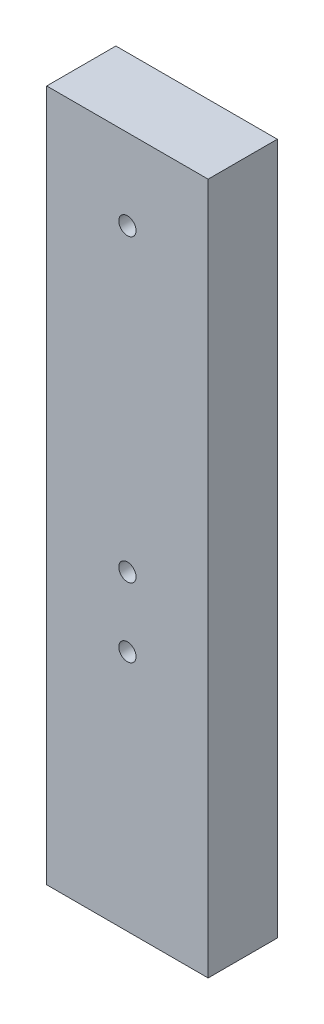
SolidWorks part; units mm, degrees
material "Oak"
ref_plane "Front" through (0, 0, 0) normal (0, 0, 1) x (1, 0, 0)
ref_plane "Top" through (0, 0, 0) normal (0, 1, 0) x (1, 0, 0)
ref_plane "Right" through (0, 0, 0) normal (1, 0, 0) x (0, 0, -1)
sketch "Sketch1" plane through (0, 0, 0) normal (0, 0, 1) x (1, 0, 0)
  line L1 (0, 0) -> (88.9, 0)
  line L2 (0, 0) -> (0, 381)
  line L3 (0, 381) -> (88.9, 381)
  line L4 (88.9, 0) -> (88.9, 381)
  dimension "D1" = 381
  dimension "D2" = 88.9
extrude "Boss-Extrude1" add sketch "Sketch1" along normal blind 38.1
sketch "Sketch2" plane through (0, 0, 38.1) normal (0, 0, 1) x (1, 0, 0)
  line L0 (0, 0) -> (88.9, 0) construction
  line L1 (88.9, 0) -> (88.9, 381) construction
  circle A0 centre (44.45, 133.35) radius 4.7625
  dimension "D3" = 9.525
  dimension "D1" = 133.35
  dimension "D2" = 44.45
extrude "Cut-Extrude1" cut sketch "Sketch2" against normal through all
sketch "Sketch3" plane through (0, 0, 38.1) normal (0, 0, 1) x (1, 0, 0)
  line L0 (88.9, 0) -> (88.9, 381) construction
  line L1 (88.9, 381) -> (0, 381) construction
  circle A0 centre (44.45, 336.55) radius 4.7625
  dimension "D3" = 9.525
  dimension "D1" = 44.45
  dimension "D2" = 44.45
extrude "Cut-Extrude2" cut sketch "Sketch3" against normal through all
sketch "Sketch4" plane through (0, 0, 38.1) normal (0, 0, 1) x (1, 0, 0)
  line L0 (0, 381) -> (0, 0) construction
  circle A0 centre (44.45, 171.45) radius 4.7625
  circle A1 centre (44.45, 133.35) radius 4.7625 construction
  dimension "D1" = 9.525
  dimension "D2" = 38.1
  dimension "D3" = 44.45
extrude "Cut-Extrude3" cut sketch "Sketch4" against normal through all
